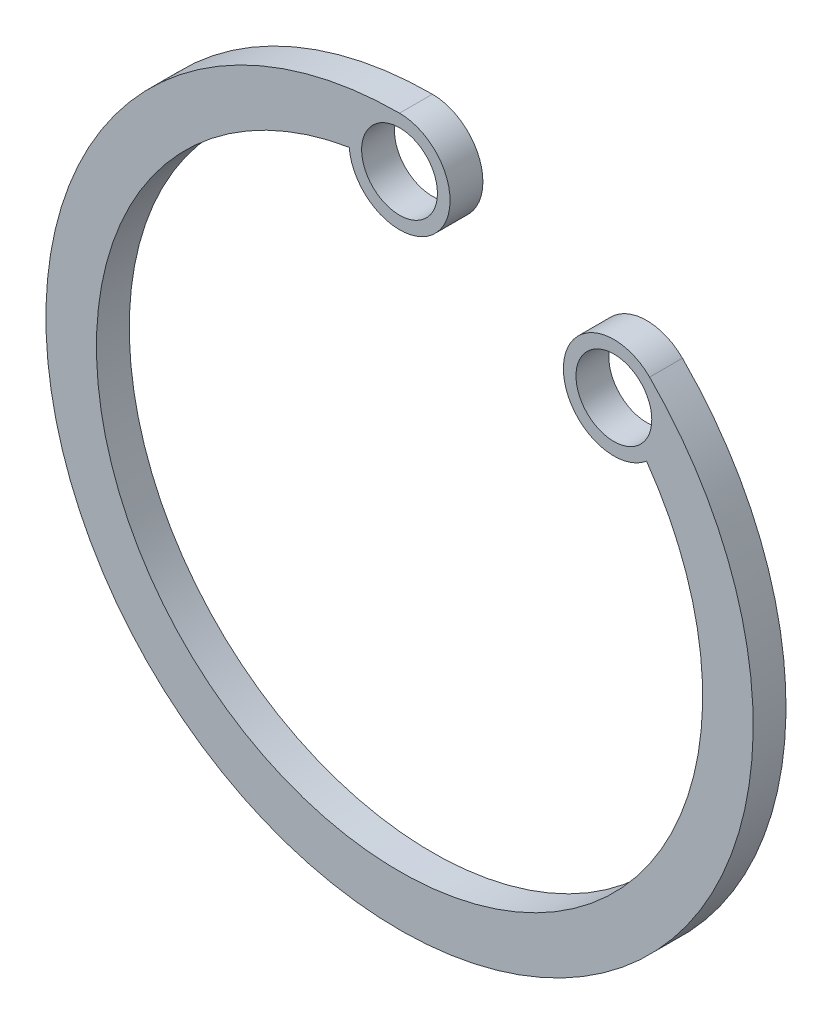
SolidWorks part; units mm, degrees
ref_plane "Front Plane" through (0, 0, 0) normal (0, 0, 1) x (1, 0, 0)
ref_plane "Top Plane" through (0, 0, 0) normal (0, 1, 0) x (1, 0, 0)
ref_plane "Right Plane" through (0, 0, 0) normal (1, 0, 0) x (0, 0, -1)
sketch "Sketch1" plane through (0, 0, 0) normal (0, 0, 1) x (1, 0, 0)
  line L0 (0, 0) -> (0, 12) construction
  line L1 (0, 0) -> (8.4853, 8.4853) construction
  line L2 (0, 0) -> (0, 12) construction
  line L3 (0, 0) -> (8.4853, 8.4853) construction
  circle A0 centre (0, 0) radius 13
  circle A1 centre (0, 0) radius 14
  circle A2 centre (0, 0) radius 12
  circle A3 centre (0, 12) radius 2
  circle A5 centre (0, 12) radius 1.5
  circle A6 centre (8.4853, 8.4853) radius 2
  circle A7 centre (8.4853, 8.4853) radius 1.5
  dimension "D1" = 26
  dimension "D4" = 4
  dimension "D5" = 3
  dimension "D6" = 2
  dimension "D7" = 45
  dimension "D2" = 1
  dimension "D3" = 1
extrude "Boss-Extrude1" add sketch "Sketch1" along normal blind 1.3 contours A6 A0 A3 A1 | A6 A2 A3 A0 | A5 A0 A3 | A5 A0 A3 A2 | A5 A2 A3 | A5 A2 A3 A0 | A7 A2 A6 A0 | A7 A2 A6 | A7 A0 A6 | A7 A0 A6 A2
